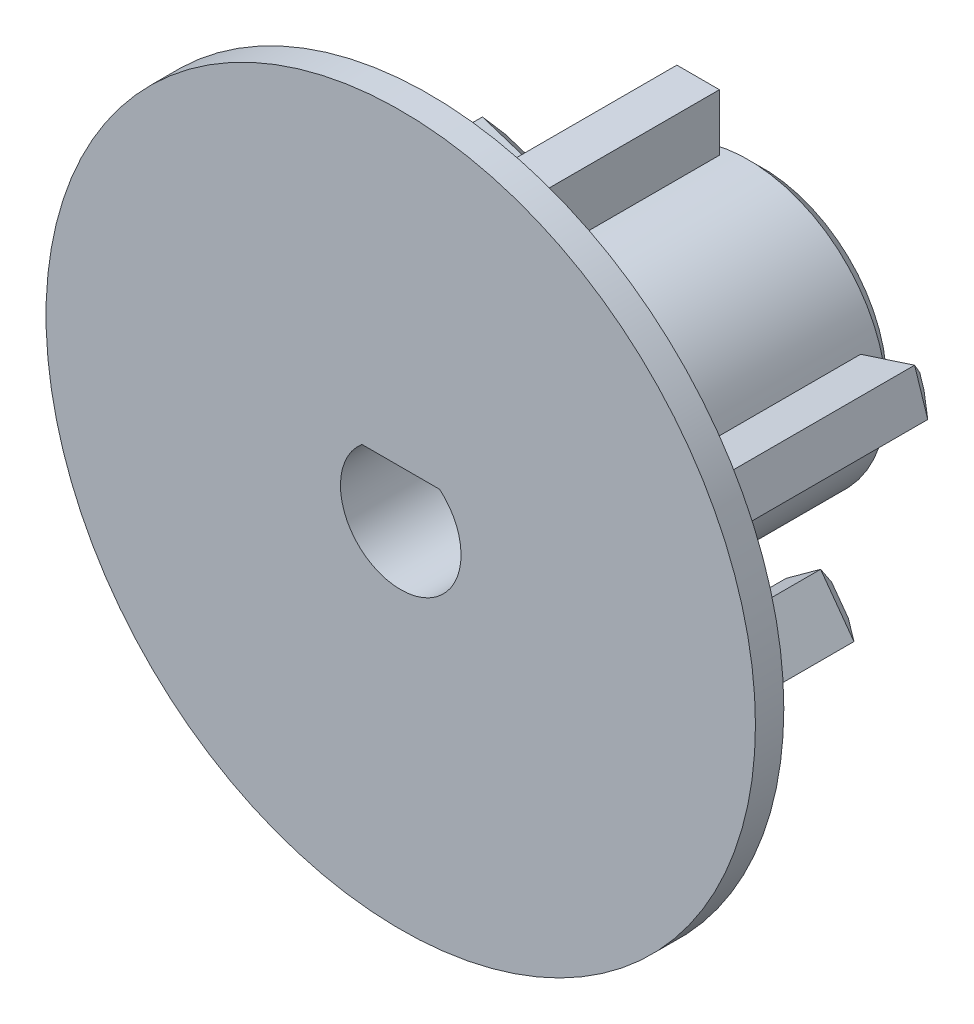
SolidWorks part; units mm, degrees
ref_plane "Plan de face" through (0, 0, 0) normal (0, 0, 1) x (1, 0, 0)
ref_plane "Plan de dessus" through (0, 0, 0) normal (0, 1, 0) x (1, 0, 0)
ref_plane "Plan de droite" through (0, 0, 0) normal (1, 0, 0) x (0, 0, -1)
sketch "Esquisse3" plane through (0, 0, 0) normal (0, 0, 1) x (1, 0, 0)
  circle A0 centre (0, 0) radius 25
  dimension "D1" = 50
extrude "Boss.-Extru.2" add sketch "Esquisse3" along normal blind 2
sketch "Esquisse5" plane through (0, 0, 0) normal (0, 0, -1) x (-1, 0, 0)
  line L0 (-15.2168, 6.5625) -> (-11.4126, 5.3264)
  line L5 (-11.4126, 5.3264) -> (-12.3397, 2.4733)
  line L6 (-12.3397, 2.4733) -> (-16.1439, 3.7093)
  line L7 (-16.1439, 3.7093) -> (-15.2168, 6.5625)
  line L8 (-1.461, 16.5) -> (1.539, 16.5)
  line L9 (1.539, 16.5) -> (1.539, 12.5)
  line L10 (1.539, 12.5) -> (-1.461, 12.5)
  line L11 (-1.461, 12.5) -> (-1.461, 16.5)
  line L12 (15.241, 6.4882) -> (16.168, 3.6351)
  line L13 (16.168, 3.6351) -> (12.3638, 2.399)
  line L14 (12.3638, 2.399) -> (11.4367, 5.2522)
  line L15 (11.4367, 5.2522) -> (15.241, 6.4882)
  line L16 (10.8804, -12.49) -> (8.4533, -14.2534)
  line L17 (8.4533, -14.2534) -> (6.1022, -11.0173)
  line L18 (6.1022, -11.0173) -> (8.5293, -9.254)
  line L19 (8.5293, -9.254) -> (10.8804, -12.49)
  line L20 (-8.5165, -14.2075) -> (-10.9436, -12.4442)
  line L21 (-10.9436, -12.4442) -> (-8.5924, -9.2081)
  line L22 (-8.5924, -9.2081) -> (-6.1654, -10.9714)
  line L23 (-6.1654, -10.9714) -> (-8.5165, -14.2075)
  circle A0 centre (0, 0) radius 9.75
  point P4 (-11.8761, 3.8998)
  point P6 (-13.3147, 5.9445)
  point P28 (0, 0)
  dimension "D2" = 4
  dimension "D3" = 12.5001
  dimension "D1" = 5
extrude "Boss.-Extru.3" add sketch "Esquisse5" along normal blind 20
sketch "Esquisse6" plane through (0, 0, 2) normal (0, 0, 1) x (1, 0, 0)
  line L0 (-2.7386, 3.25) -> (2.7386, 3.25)
  arc A0 (-2.7386, 3.25) -> (2.7386, 3.25) centre (0, 0) ccw
  dimension "D1" = 8.5
  dimension "D2" = 3.25
extrude "Enlèv. mat.-Extru.1" cut sketch "Esquisse6" against normal blind 22
sketch "Esquisse7" plane through (0, 0, -20) normal (0, 0, -1) x (-1, 0, 0)
  circle A0 centre (0, 0) radius 9.75
extrude "Boss.-Extru.4" add sketch "Esquisse7" along normal blind 3.5
sketch "Esquisse8" plane through (0, 0, -23.5) normal (0, 0, -1) x (-1, 0, 0)
  circle A0 centre (0, 0) radius 1.25
  dimension "D1" = 2.5
extrude "Enlèv. mat.-Extru.2" cut sketch "Esquisse8" against normal through all
chamfer "Chanfrein3" distance 1 angle 45 4 edges at (11.8761, 3.8998, -20) (13.3147, 5.9445, -20) (15.6804, 5.1359, -20) (14.2418, 3.0913, -20)
chamfer "Chanfrein4" distance 1 angle 45 17 edges at (-9.75, 0, -23.5) (-0.039, 12.5, -20) (-1.539, 14.5, -20) (-0.039, 16.5, -20) (1.461, 14.5, -20) (-11.9003, 3.8256, -20) (-13.3389, 5.8702, -20) (-15.7045, 5.0617, -20) (-14.2659, 3.017, -20) (-9.7048, -10.872, -20) (-7.3157, -10.1357, -20) (-7.2778, -12.6354, -20) (-9.6669, -13.3717, -20) (7.3789, -10.0898, -20) (7.3409, -12.5895, -20) (9.73, -13.3258, -20) (9.768, -10.8261, -20)
chamfer "Chanfrein5" distance 0.5 angle 45 1 edges at (-1.25, 0, -20)
equation "\"3.5.00mm\"=4"
